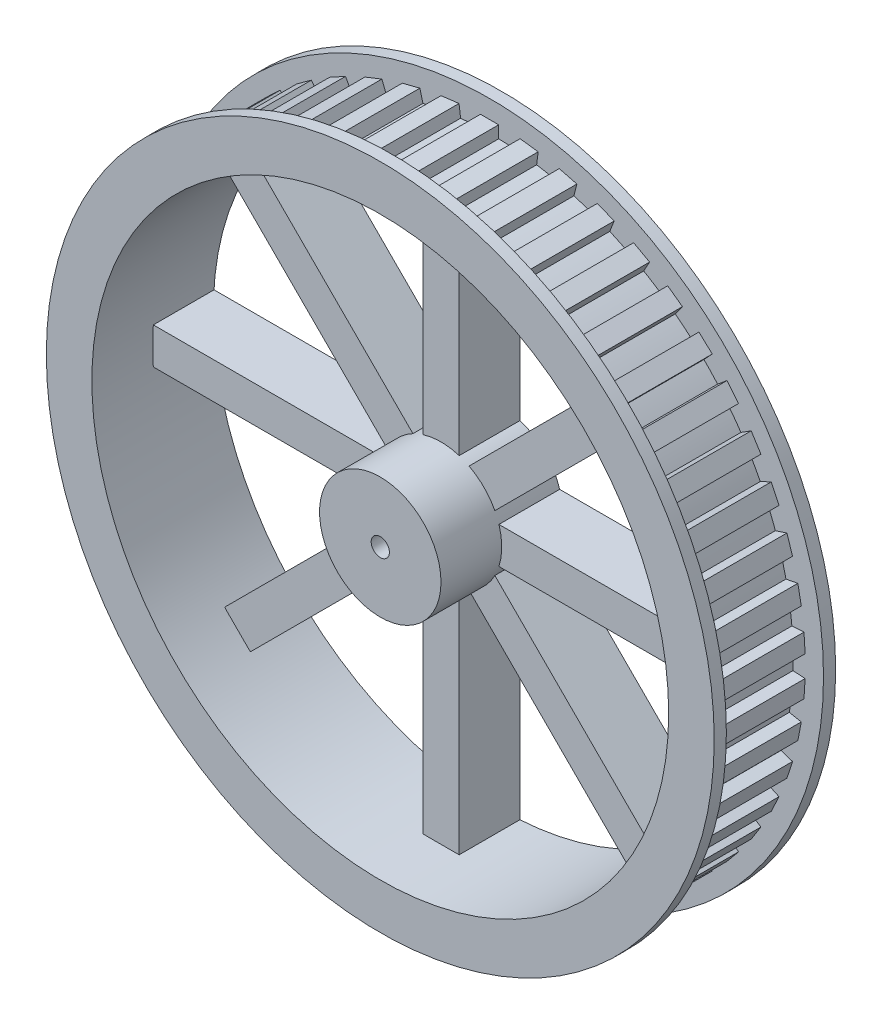
SolidWorks part; units mm, degrees
ref_plane "Front Plane" through (0, 0, 0) normal (0, 0, 1) x (1, 0, 0)
ref_plane "Top Plane" through (0, 0, 0) normal (0, 1, 0) x (1, 0, 0)
ref_plane "Right Plane" through (0, 0, 0) normal (1, 0, 0) x (0, 0, -1)
sketch "Sketch1" plane through (0, 0, 0) normal (0, 0, 1) x (1, 0, 0)
  circle A0 centre (0, 0) radius 10
  dimension "D1" = 20
extrude "Boss-Extrude1" add sketch "Sketch1" along normal blind 20
sketch "Sketch2" plane through (0, 0, 0) normal (0, 0, 1) x (1, 0, 0)
  circle A0 centre (0, 0) radius 55
  circle A1 centre (0, 0) radius 47.5
  dimension "D1" = 110
  dimension "D2" = 95
extrude "Boss-Extrude2" add sketch "Sketch2" along normal blind 2 separate body
sketch "Sketch3" plane through (0, 0, 0) normal (0, 0, 1) x (1, 0, 0)
  line L0 (0, -55) -> (0, 55) construction
  line L1 (-1.5, 49.9775) -> (1.5, 49.9775)
  line L2 (-1.5, 49.9775) -> (-1.5, 51.9775)
  line L3 (-1.5, 51.9775) -> (1.5, 51.9775)
  line L4 (1.5, 49.9775) -> (1.5, 51.9775)
  line L5 (4.7757, 49.7714) -> (5.0263, 51.7556)
  line L6 (4.7757, 49.7714) -> (7.752, 49.3954)
  line L7 (7.752, 49.3954) -> (8.0027, 51.3796)
  line L8 (5.0263, 51.7556) -> (8.0027, 51.3796)
  line L9 (10.976, 48.7804) -> (11.4734, 50.7176)
  line L10 (10.976, 48.7804) -> (13.8818, 48.0343)
  line L11 (13.8818, 48.0343) -> (14.3792, 49.9715)
  line L12 (11.4734, 50.7176) -> (14.3792, 49.9715)
  line L13 (17.0033, 47.0201) -> (17.7395, 48.8796)
  line L14 (17.0033, 47.0201) -> (19.7926, 45.9157)
  line L15 (19.7926, 45.9157) -> (20.5289, 47.7753)
  line L16 (17.7395, 48.8796) -> (20.5289, 47.7753)
  line L17 (22.7624, 44.5182) -> (23.7259, 46.2709)
  line L18 (22.7624, 44.5182) -> (25.3913, 43.073)
  line L19 (25.3913, 43.073) -> (26.3548, 44.8256)
  line L20 (23.7259, 46.2709) -> (26.3548, 44.8256)
  line L21 (28.1625, 41.3143) -> (29.3381, 42.9324)
  line L22 (28.1625, 41.3143) -> (30.5896, 39.551)
  line L23 (30.5896, 39.551) -> (31.7651, 41.169)
  line L24 (29.3381, 42.9324) -> (31.7651, 41.169)
  line L25 (33.1185, 37.4588) -> (34.4876, 38.9168)
  line L26 (33.1185, 37.4588) -> (35.3054, 35.4052)
  line L27 (35.3054, 35.4052) -> (36.6745, 36.8631)
  line L28 (34.4876, 38.9168) -> (36.6745, 36.8631)
  line L29 (37.5522, 33.0126) -> (39.0932, 34.2875)
  line L30 (37.5522, 33.0126) -> (39.4645, 30.7011)
  line L31 (39.4645, 30.7011) -> (41.0055, 31.9759)
  line L32 (39.0932, 34.2875) -> (41.0055, 31.9759)
  line L33 (41.3937, 28.0458) -> (43.0823, 29.1174)
  line L34 (41.3937, 28.0458) -> (43.0011, 25.5128)
  line L35 (43.0011, 25.5128) -> (44.6898, 26.5844)
  line L36 (43.0823, 29.1174) -> (44.6898, 26.5844)
  line L37 (44.5823, 22.6366) -> (46.392, 23.4882)
  line L38 (44.5823, 22.6366) -> (45.8597, 19.9221)
  line L39 (45.8597, 19.9221) -> (47.6693, 20.7737)
  line L40 (46.392, 23.4882) -> (47.6693, 20.7737)
  line L41 (47.0679, 16.8705) -> (48.97, 17.4885)
  line L42 (47.0679, 16.8705) -> (47.9949, 14.0173)
  line L43 (47.9949, 14.0173) -> (49.8971, 14.6353)
  line L44 (48.97, 17.4885) -> (49.8971, 14.6353)
  line L45 (48.8112, 10.8383) -> (50.7758, 11.213)
  line L46 (48.8112, 10.8383) -> (49.3733, 7.8914)
  line L47 (49.3733, 7.8914) -> (51.3379, 8.2662)
  line L48 (50.7758, 11.213) -> (51.3379, 8.2662)
  line L49 (49.7847, 4.6352) -> (51.7807, 4.7607)
  line L50 (49.7847, 4.6352) -> (49.9731, 1.6411)
  line L51 (49.9731, 1.6411) -> (51.9691, 1.7667)
  line L52 (51.7807, 4.7607) -> (51.9691, 1.7667)
  line L53 (49.9731, -1.6411) -> (51.9691, -1.7667)
  line L54 (49.9731, -1.6411) -> (49.7847, -4.6352)
  line L55 (49.7847, -4.6352) -> (51.7807, -4.7607)
  line L56 (51.9691, -1.7667) -> (51.7807, -4.7607)
  line L57 (49.3733, -7.8914) -> (51.3379, -8.2662)
  line L58 (49.3733, -7.8914) -> (48.8112, -10.8383)
  line L59 (48.8112, -10.8383) -> (50.7758, -11.213)
  line L60 (51.3379, -8.2662) -> (50.7758, -11.213)
  line L61 (47.9949, -14.0173) -> (49.8971, -14.6353)
  line L62 (47.9949, -14.0173) -> (47.0679, -16.8705)
  line L63 (47.0679, -16.8705) -> (48.97, -17.4885)
  line L64 (49.8971, -14.6353) -> (48.97, -17.4885)
  line L65 (45.8597, -19.9221) -> (47.6693, -20.7737)
  line L66 (45.8597, -19.9221) -> (44.5823, -22.6366)
  line L67 (44.5823, -22.6366) -> (46.392, -23.4882)
  line L68 (47.6693, -20.7737) -> (46.392, -23.4882)
  line L69 (43.0011, -25.5128) -> (44.6898, -26.5844)
  line L70 (43.0011, -25.5128) -> (41.3937, -28.0458)
  line L71 (41.3937, -28.0458) -> (43.0823, -29.1174)
  line L72 (44.6898, -26.5844) -> (43.0823, -29.1174)
  line L73 (39.4645, -30.7011) -> (41.0055, -31.9759)
  line L74 (39.4645, -30.7011) -> (37.5522, -33.0126)
  line L75 (37.5522, -33.0126) -> (39.0932, -34.2875)
  line L76 (41.0055, -31.9759) -> (39.0932, -34.2875)
  line L77 (35.3054, -35.4052) -> (36.6745, -36.8631)
  line L78 (35.3054, -35.4052) -> (33.1185, -37.4588)
  line L79 (33.1185, -37.4588) -> (34.4876, -38.9168)
  line L80 (36.6745, -36.8631) -> (34.4876, -38.9168)
  line L81 (30.5896, -39.551) -> (31.7651, -41.169)
  line L82 (30.5896, -39.551) -> (28.1625, -41.3143)
  line L83 (28.1625, -41.3143) -> (29.3381, -42.9324)
  line L84 (31.7651, -41.169) -> (29.3381, -42.9324)
  line L85 (25.3913, -43.073) -> (26.3548, -44.8256)
  line L86 (25.3913, -43.073) -> (22.7624, -44.5182)
  line L87 (22.7624, -44.5182) -> (23.7259, -46.2709)
  line L88 (26.3548, -44.8256) -> (23.7259, -46.2709)
  line L89 (19.7926, -45.9157) -> (20.5289, -47.7753)
  line L90 (19.7926, -45.9157) -> (17.0033, -47.0201)
  line L91 (17.0033, -47.0201) -> (17.7395, -48.8796)
  line L92 (20.5289, -47.7753) -> (17.7395, -48.8796)
  line L93 (13.8818, -48.0343) -> (14.3792, -49.9715)
  line L94 (13.8818, -48.0343) -> (10.976, -48.7804)
  line L95 (10.976, -48.7804) -> (11.4734, -50.7176)
  line L96 (14.3792, -49.9715) -> (11.4734, -50.7176)
  line L97 (7.752, -49.3954) -> (8.0027, -51.3796)
  line L98 (7.752, -49.3954) -> (4.7757, -49.7714)
  line L99 (4.7757, -49.7714) -> (5.0263, -51.7556)
  line L100 (8.0027, -51.3796) -> (5.0263, -51.7556)
  line L101 (1.5, -49.9775) -> (1.5, -51.9775)
  line L102 (1.5, -49.9775) -> (-1.5, -49.9775)
  line L103 (-1.5, -49.9775) -> (-1.5, -51.9775)
  line L104 (1.5, -51.9775) -> (-1.5, -51.9775)
  line L105 (-4.7757, -49.7714) -> (-5.0263, -51.7556)
  line L106 (-4.7757, -49.7714) -> (-7.752, -49.3954)
  line L107 (-7.752, -49.3954) -> (-8.0027, -51.3796)
  line L108 (-5.0263, -51.7556) -> (-8.0027, -51.3796)
  line L109 (-10.976, -48.7804) -> (-11.4734, -50.7176)
  line L110 (-10.976, -48.7804) -> (-13.8818, -48.0343)
  line L111 (-13.8818, -48.0343) -> (-14.3792, -49.9715)
  line L112 (-11.4734, -50.7176) -> (-14.3792, -49.9715)
  line L113 (-17.0033, -47.0201) -> (-17.7395, -48.8796)
  line L114 (-17.0033, -47.0201) -> (-19.7926, -45.9157)
  line L115 (-19.7926, -45.9157) -> (-20.5289, -47.7753)
  line L116 (-17.7395, -48.8796) -> (-20.5289, -47.7753)
  line L117 (-22.7624, -44.5182) -> (-23.7259, -46.2709)
  line L118 (-22.7624, -44.5182) -> (-25.3913, -43.073)
  line L119 (-25.3913, -43.073) -> (-26.3548, -44.8256)
  line L120 (-23.7259, -46.2709) -> (-26.3548, -44.8256)
  line L121 (-28.1625, -41.3143) -> (-29.3381, -42.9324)
  line L122 (-28.1625, -41.3143) -> (-30.5896, -39.551)
  line L123 (-30.5896, -39.551) -> (-31.7651, -41.169)
  line L124 (-29.3381, -42.9324) -> (-31.7651, -41.169)
  line L125 (-33.1185, -37.4588) -> (-34.4876, -38.9168)
  line L126 (-33.1185, -37.4588) -> (-35.3054, -35.4052)
  line L127 (-35.3054, -35.4052) -> (-36.6745, -36.8631)
  line L128 (-34.4876, -38.9168) -> (-36.6745, -36.8631)
  line L129 (-37.5522, -33.0126) -> (-39.0932, -34.2875)
  line L130 (-37.5522, -33.0126) -> (-39.4645, -30.7011)
  line L131 (-39.4645, -30.7011) -> (-41.0055, -31.9759)
  line L132 (-39.0932, -34.2875) -> (-41.0055, -31.9759)
  line L133 (-41.3937, -28.0458) -> (-43.0823, -29.1174)
  line L134 (-41.3937, -28.0458) -> (-43.0011, -25.5128)
  line L135 (-43.0011, -25.5128) -> (-44.6898, -26.5844)
  line L136 (-43.0823, -29.1174) -> (-44.6898, -26.5844)
  line L137 (-44.5823, -22.6366) -> (-46.392, -23.4882)
  line L138 (-44.5823, -22.6366) -> (-45.8597, -19.9221)
  line L139 (-45.8597, -19.9221) -> (-47.6693, -20.7737)
  line L140 (-46.392, -23.4882) -> (-47.6693, -20.7737)
  line L141 (-47.0679, -16.8705) -> (-48.97, -17.4885)
  line L142 (-47.0679, -16.8705) -> (-47.9949, -14.0173)
  line L143 (-47.9949, -14.0173) -> (-49.8971, -14.6353)
  line L144 (-48.97, -17.4885) -> (-49.8971, -14.6353)
  line L145 (-48.8112, -10.8383) -> (-50.7758, -11.213)
  line L146 (-48.8112, -10.8383) -> (-49.3733, -7.8914)
  line L147 (-49.3733, -7.8914) -> (-51.3379, -8.2662)
  line L148 (-50.7758, -11.213) -> (-51.3379, -8.2662)
  line L149 (-49.7847, -4.6352) -> (-51.7807, -4.7607)
  line L150 (-49.7847, -4.6352) -> (-49.9731, -1.6411)
  line L151 (-49.9731, -1.6411) -> (-51.9691, -1.7667)
  line L152 (-51.7807, -4.7607) -> (-51.9691, -1.7667)
  line L153 (-49.9731, 1.6411) -> (-51.9691, 1.7667)
  line L154 (-49.9731, 1.6411) -> (-49.7847, 4.6352)
  line L155 (-49.7847, 4.6352) -> (-51.7807, 4.7607)
  line L156 (-51.9691, 1.7667) -> (-51.7807, 4.7607)
  line L157 (-49.3733, 7.8914) -> (-51.3379, 8.2662)
  line L158 (-49.3733, 7.8914) -> (-48.8112, 10.8383)
  line L159 (-48.8112, 10.8383) -> (-50.7758, 11.213)
  line L160 (-51.3379, 8.2662) -> (-50.7758, 11.213)
  line L161 (-47.9949, 14.0173) -> (-49.8971, 14.6353)
  line L162 (-47.9949, 14.0173) -> (-47.0679, 16.8705)
  line L163 (-47.0679, 16.8705) -> (-48.97, 17.4885)
  line L164 (-49.8971, 14.6353) -> (-48.97, 17.4885)
  line L165 (-45.8597, 19.9221) -> (-47.6693, 20.7737)
  line L166 (-45.8597, 19.9221) -> (-44.5823, 22.6366)
  line L167 (-44.5823, 22.6366) -> (-46.392, 23.4882)
  line L168 (-47.6693, 20.7737) -> (-46.392, 23.4882)
  line L169 (-43.0011, 25.5128) -> (-44.6898, 26.5844)
  line L170 (-43.0011, 25.5128) -> (-41.3937, 28.0458)
  line L171 (-41.3937, 28.0458) -> (-43.0823, 29.1174)
  line L172 (-44.6898, 26.5844) -> (-43.0823, 29.1174)
  line L173 (-39.4645, 30.7011) -> (-41.0055, 31.9759)
  line L174 (-39.4645, 30.7011) -> (-37.5522, 33.0126)
  line L175 (-37.5522, 33.0126) -> (-39.0932, 34.2875)
  line L176 (-41.0055, 31.9759) -> (-39.0932, 34.2875)
  line L177 (-35.3054, 35.4052) -> (-36.6745, 36.8631)
  line L178 (-35.3054, 35.4052) -> (-33.1185, 37.4588)
  line L179 (-33.1185, 37.4588) -> (-34.4876, 38.9168)
  line L180 (-36.6745, 36.8631) -> (-34.4876, 38.9168)
  line L181 (-30.5896, 39.551) -> (-31.7651, 41.169)
  line L182 (-30.5896, 39.551) -> (-28.1625, 41.3143)
  line L183 (-28.1625, 41.3143) -> (-29.3381, 42.9324)
  line L184 (-31.7651, 41.169) -> (-29.3381, 42.9324)
  line L185 (-25.3913, 43.073) -> (-26.3548, 44.8256)
  line L186 (-25.3913, 43.073) -> (-22.7624, 44.5182)
  line L187 (-22.7624, 44.5182) -> (-23.7259, 46.2709)
  line L188 (-26.3548, 44.8256) -> (-23.7259, 46.2709)
  line L189 (-19.7926, 45.9157) -> (-20.5289, 47.7753)
  line L190 (-19.7926, 45.9157) -> (-17.0033, 47.0201)
  line L191 (-17.0033, 47.0201) -> (-17.7395, 48.8796)
  line L192 (-20.5289, 47.7753) -> (-17.7395, 48.8796)
  line L193 (-13.8818, 48.0343) -> (-14.3792, 49.9715)
  line L194 (-13.8818, 48.0343) -> (-10.976, 48.7804)
  line L195 (-10.976, 48.7804) -> (-11.4734, 50.7176)
  line L196 (-14.3792, 49.9715) -> (-11.4734, 50.7176)
  line L197 (-7.752, 49.3954) -> (-8.0027, 51.3796)
  line L198 (-7.752, 49.3954) -> (-4.7757, 49.7714)
  line L199 (-4.7757, 49.7714) -> (-5.0263, 51.7556)
  line L200 (-8.0027, 51.3796) -> (-5.0263, 51.7556)
  circle A0 centre (0, 0) radius 50
  circle A1 centre (0, 0) radius 47.5
  point P208 (0, 0)
  dimension "D1" = 100
  dimension "D2" = 95
  dimension "D3" = 3
  dimension "D4" = 2
  dimension "D5" = 1.5
  dimension "D6" = 50
extrude "Boss-Extrude3" add sketch "Sketch3" along normal blind 20 contours A0 L183 L184 L181 | A0 L151 L152 L149 | A1 | A0 L55 L56 L53 | A0 L4 L3 L2 | L186 L187 L188 L185 | L180 L179 L178 L177 | L176 L175 L174 L173 | L172 L171 L170 L169 | L168 L167 L166 L165 | L162 L163 L164 L161 | L157 L160 L159 L158 | L154 L155 L156 L153 | L148 L147 L146 L145 | L141 L144 L143 L142 | L137 L140 L139 L138 | L135 L136 L133 L134 | L129 L132 L131 L130 | L125 L128 L127 L126 | L121 L124 L123 L122 | L117 L120 L119 L118 | L114 L115 L116 L113 | L112 L111 L110 L109 | L108 L107 L106 L105 | L104 L103 L102 L101 | L98 L99 L100 L97 | L93 L96 L95 L94 | L90 L91 L92 L89 | L85 L88 L87 L86 | L81 L84 L83 L82 | L77 L80 L79 L78 | L73 L76 L75 L74 | L69 L72 L71 L70 | L65 L68 L67 L66 | L62 L63 L64 L61 | L58 L59 L60 L57 | L52 L51 L50 L49 | L47 L48 L45 L46 | L42 L43 L44 L41 | L37 L40 L39 L38 | L35 L36 L33 L34 | L29 L32 L31 L30 | L27 L28 L25 L26 | L21 L24 L23 L22 | L18 L19 L20 L17 | L14 L15 L16 L13 | L9 L12 L11 L10 | L6 L7 L8 L5 | L197 L200 L199 L198 | L196 L195 L194 L193 | L190 L191 L192 L189
sketch "Sketch4" plane through (0, 0, 20) normal (0, 0, 1) x (1, 0, 0)
  circle A0 centre (0, 0) radius 55
  circle A1 centre (0, 0) radius 47.5
  dimension "D1" = 110
  dimension "D2" = 95
extrude "Boss-Extrude4" add sketch "Sketch4" against normal blind 2
sketch "Sketch5" plane through (0, 0, 0) normal (0, 0, 1) x (1, 0, 0)
  circle A0 centre (0, 0) radius 1.5
  dimension "D1" = 3
extrude "Cut-Extrude2" cut sketch "Sketch5" along normal blind 30 and the other way through all
sketch "Sketch6" plane through (0, 0, 0) normal (0, 0, 1) x (1, 0, 0)
  line L0 (0, -55) -> (0, 55) construction
  line L1 (-3, 9.5394) -> (3, 9.5394)
  line L2 (-3, 9.5394) -> (-3, 47.4052)
  line L3 (-3, 47.4052) -> (3, 47.4052)
  line L4 (3, 9.5394) -> (3, 47.4052)
  circle A0 centre (0, 0) radius 10 construction
  circle A1 centre (0, 0) radius 47.5 construction
  dimension "D1" = 6
  dimension "D2" = 3
extrude "Boss-Extrude6" add sketch "Sketch6" along normal blind 10
pattern_circular "CirPattern1" count 8 over 360 about axis through (0, 0, 0) along (0, 0, 1) of "Boss-Extrude6"
